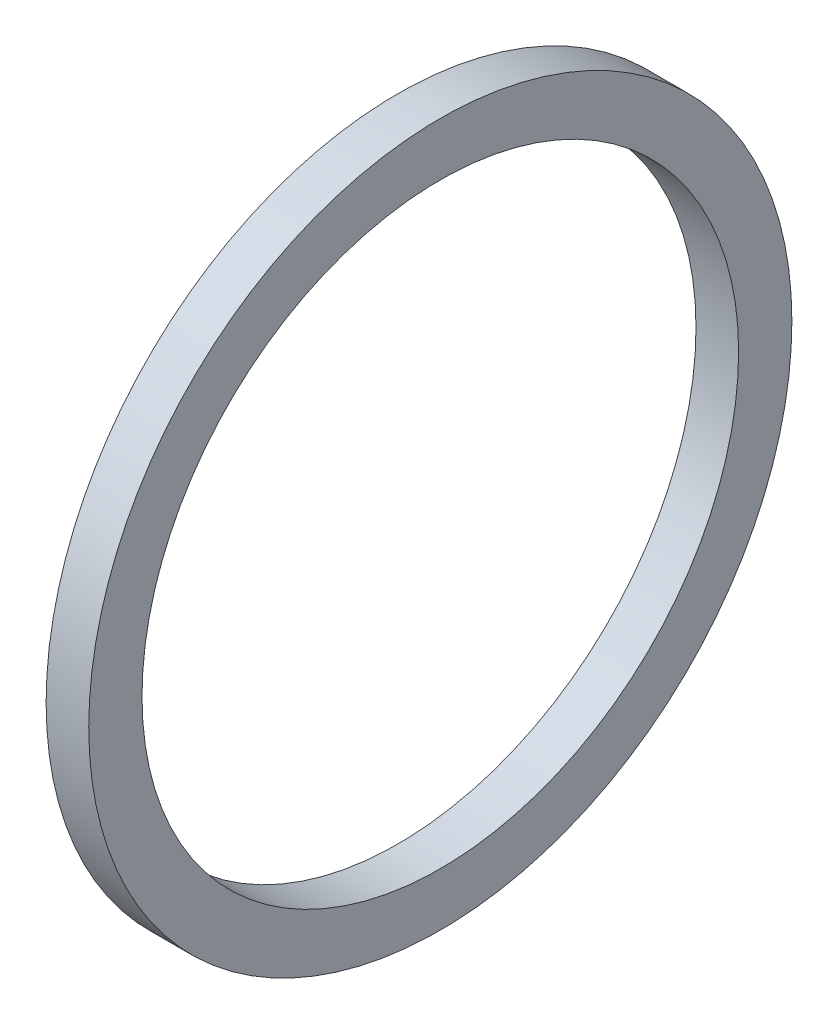
SolidWorks part; units mm, degrees
ref_plane "Front Plane" through (0, 0, 0) normal (0, 0, 1) x (1, 0, 0)
ref_plane "Top Plane" through (0, 0, 0) normal (0, 1, 0) x (1, 0, 0)
ref_plane "Right Plane" through (0, 0, 0) normal (1, 0, 0) x (0, 0, -1)
sketch "Axial profile (mm)" plane through (0, 0, 0) normal (0, 0, 1) x (1, 0, 0)
  line L0 (-110, 0) -> (75, 0) construction
  line L1 (-1, 14) -> (1, 14)
  line L2 (1, 14) -> (1, 16.5)
  line L3 (1, 16.5) -> (-1, 16.5)
  line L4 (-1, 16.5) -> (-1, 14)
revolve "Full revolution" add sketch "Axial profile (mm)" angle 360 about L0
